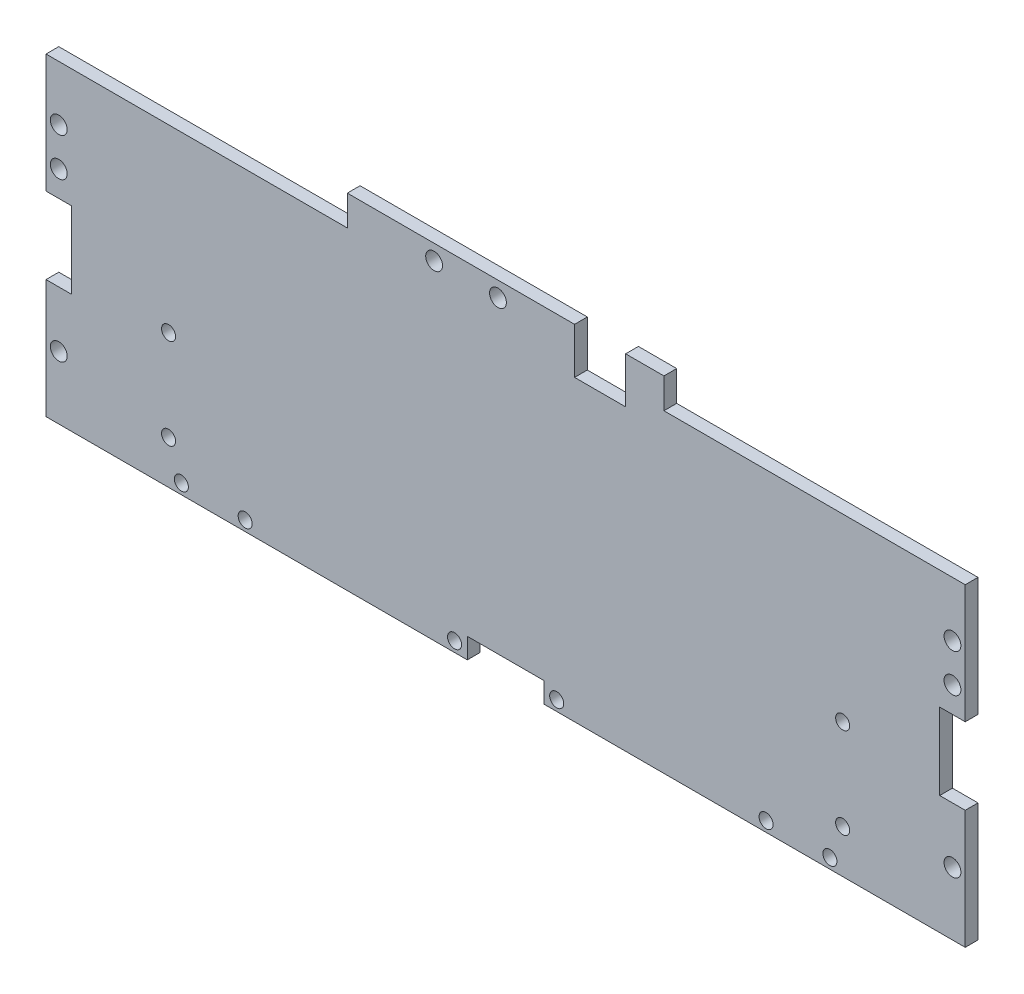
SolidWorks part; units mm, degrees
material "7075-T6, Chapa (SS)"
ref_plane "Plano frontal" through (0, 0, 0) normal (0, 0, 1) x (1, 0, 0)
ref_plane "Plano superior" through (0, 0, 0) normal (0, 1, 0) x (1, 0, 0)
ref_plane "Plano direito" through (0, 0, 0) normal (1, 0, 0) x (0, 0, -1)
sketch "Esboço1" plane through (0, 0, 0) normal (0, 0, 1) x (1, 0, 0)
  line L0 (0, 76.5) -> (0, 132.32)
  line L1 (0, 0) -> (165, 0)
  line L2 (0, 0) -> (0, 46.5)
  line L3 (116, 134.82) -> (244, 134.82)
  line L4 (360, 0) -> (360, 46.5)
  line L5 (0, 46.5) -> (10, 46.5)
  line L7 (0, 76.5) -> (10, 76.5)
  line L8 (10, 46.5) -> (10, 76.5)
  line L9 (360, 76.5) -> (360, 132.32)
  line L10 (360, 46.5) -> (350, 46.5)
  line L12 (360, 76.5) -> (350, 76.5)
  line L13 (350, 46.5) -> (350, 76.5)
  line L14 (195, 0) -> (360, 0)
  line L16 (165, 0) -> (165, 8)
  line L17 (165, 8) -> (195, 8)
  line L18 (195, 0) -> (195, 8)
  line L21 (0, 132.32) -> (0, 172.82)
  line L22 (0, 172.82) -> (116, 172.82)
  line L23 (116, 134.82) -> (116, 172.82)
  line L25 (360, 132.32) -> (360, 172.82)
  line L26 (360, 172.82) -> (244, 172.82)
  line L27 (244, 134.82) -> (244, 172.82)
  dimension "D1" = 360
  dimension "D2" = 132.32
  dimension "D3" = 10
  dimension "D4" = 30
  dimension "D5" = 46.5
  dimension "D6" = 30
  dimension "D7" = 10
  dimension "D8" = 46.5
  dimension "D9" = 8
  dimension "D10" = 30
  dimension "D11" = 128
  dimension "D12" = 40.5
  dimension "D13" = 38
extrude "Ressalto-extrusão1" add sketch "Esboço1" along normal blind 5
hole_wizard "Furo com folga de M61" positions "Esboço2" profile "Esboço3" hole size "M6" standard "ISO" end condition through all
sketch "Esboço2" plane through (-158.2782, -245.4192, 5) normal (0, 0, 1) x (-1, 0, 0)
  line L4 (-158.2782, -291.9192) -> (-158.2782, -245.4192) construction
  line L5 (-158.2782, -418.2392) -> (-158.2782, -321.9192) construction
  line L6 (-158.2782, -245.4192) -> (-323.2782, -245.4192) construction
  line L8 (-158.2782, -321.9192) -> (-168.2782, -321.9192) construction
  line L9 (-338.2782, -253.4192) -> (-338.2782, -380.2392) construction
  line L10 (-323.2782, -253.4192) -> (-353.2782, -253.4192) construction
  line L11 (-402.2782, -380.2392) -> (-274.2782, -380.2392) construction
  line L13 (-158.2782, -418.2392) -> (-158.2782, -321.9192) construction
  line L14 (-353.2782, -245.4192) -> (-518.2782, -245.4192) construction
  line L15 (-518.2782, -321.9192) -> (-518.2782, -418.2392) construction
  line L16 (-458.2782, -374.2392) -> (-218.2782, -374.2392) construction
  line L17 (-168.2782, -291.9192) -> (-158.2782, -291.9192) construction
  line L18 (-402.2782, -418.2392) -> (-402.2782, -380.2392) construction
  point P3 (-163.2782, -331.9192)
  point P54 (-163.2782, -270.0692)
  point P75 (-513.2782, -331.9192)
  point P76 (-513.2782, -270.0692)
  point P80 (-458.2782, -374.2392)
  point P82 (-428.2782, -374.2392)
  point P84 (-248.2782, -374.2392)
  point P86 (-218.2782, -374.2392)
  point P106 (-335.2782, -374.2392)
  point P121 (-163.2782, -346.9192)
  point P123 (-513.2782, -346.9192)
  point P130 (-310.2782, -374.2392)
  dimension "D2" = 21.85
  dimension "D3" = 5
  dimension "D4" = 15
  dimension "D5" = 128.82
  dimension "D6" = 5
  dimension "D7" = 10
  dimension "D8" = 5
  dimension "D9" = 67
  dimension "D10" = 25
  dimension "D11" = 128.82
  dimension "D12" = 128.82
  dimension "D13" = 128.82
  dimension "D14" = 60
  dimension "D15" = 60
  dimension "D16" = 30
  dimension "D17" = 30
sketch "Esboço3" plane through (5, 86.5, 5) normal (1, 0, 0) x (0, -1, 0)
  line L0 (0, 0) -> (0, 5)
  line L1 (0, 5) -> (3.3, 5)
  line L2 (3.3, 5) -> (3.3, 0)
  line L5 (3.3, 0) -> (0, 0)
  line L11 (0, -6.35) -> (0, 107.95) construction
  dimension "Thru Hole Dia." = 6.6
  dimension "Thru Hole Depth" = 5
hole_wizard "Furo com folga de M51" positions "Esboço4" profile "Esboço5" hole size "M5" standard "ISO" end condition through all
sketch "Esboço4" plane through (-158.2782, -245.4192, 5) normal (0, 0, 1) x (-1, 0, 0)
  line L0 (-470.2782, -262.4192) -> (-470.2782, -297.9192) construction
  line L1 (-470.2782, -297.9564) -> (-470.2782, -297.9192) construction
  line L2 (-206.2782, -262.4192) -> (-206.2782, -297.9192) construction
  line L5 (-518.2782, -245.4192) -> (-518.2782, -291.9192) construction
  line L6 (-158.2782, -291.9192) -> (-158.2782, -245.4192) construction
  line L8 (-353.2782, -245.4192) -> (-518.2782, -245.4192) construction
  line L9 (-158.2782, -245.4192) -> (-323.2782, -245.4192) construction
  line L11 (-518.2782, -249.4192) -> (-158.2782, -249.4192) construction
  line L12 (-518.2782, -245.4192) -> (-518.2782, -291.9192) construction
  line L14 (-353.2782, -253.4192) -> (-353.2782, -245.4192) construction
  line L15 (-323.2782, -245.4192) -> (-323.2782, -253.4192) construction
  point P0 (-470.2782, -297.9192)
  point P6 (-470.2782, -262.4192)
  point P12 (-206.2782, -297.9192)
  point P15 (-206.2782, -262.4192)
  point P78 (-465.2782, -249.4192)
  point P80 (-440.2782, -249.4192)
  point P82 (-358.2782, -249.4192)
  point P84 (-318.2782, -249.4192)
  point P86 (-236.2782, -249.4192)
  point P88 (-211.2782, -249.4192)
  dimension "D1" = 48
  dimension "D2" = 48
  dimension "D3" = 17
  dimension "D4" = 17
  dimension "D5" = 35.5
  dimension "D7" = 35.5
  dimension "D11" = 4
  dimension "D12" = 53
  dimension "D13" = 5
  dimension "D14" = 5
  dimension "D15" = 53
  dimension "D16" = 25
  dimension "D17" = 25
sketch "Esboço5" plane through (312, 52.5, 5) normal (1, 0, 0) x (0, -1, 0)
  line L0 (0, 0) -> (0, 5)
  line L1 (0, 5) -> (2.75, 5)
  line L2 (2.75, 5) -> (2.75, 0)
  line L3 (2.75, 0) -> (0, 0)
  line L4 (0, -6.35) -> (0, 107.95) construction
  dimension "Thru Hole Dia." = 5.5
  dimension "Thru Hole Depth" = 5
sketch "Esboço15" plane through (0, 0, 5) normal (0, 0, 1) x (1, 0, 0)
  line L0 (100, 172.82) -> (100, 212.82)
  line L1 (116, 172.82) -> (0, 172.82) construction
  line L2 (100, 212.82) -> (0, 172.82)
  line L3 (260, 172.82) -> (260, 212.82)
  line L4 (360, 172.82) -> (244, 172.82) construction
  line L5 (260, 212.82) -> (360, 172.82)
  line L6 (360, 172.82) -> (260, 172.82)
  line L7 (100, 172.82) -> (0, 172.82)
  dimension "D1" = 40
  dimension "D2" = 100
  dimension "D3" = 100
extrude "Ressalto-extrusão3" add sketch "Esboço15" against normal through all
sketch "Esboço18" plane through (0, 0, 5) normal (0, 0, 1) x (1, 0, 0)
  line L0 (118, 134.82) -> (118, 123)
  line L1 (118, 123) -> (0, 123)
  line L2 (0, 172.82) -> (0, 76.5) construction
  line L3 (0, 123) -> (0, 223)
  line L4 (0, 223) -> (360, 223)
  line L5 (360, 223) -> (360, 123)
  line L6 (360, 76.5) -> (360, 172.82) construction
  line L7 (360, 123) -> (242, 123)
  line L8 (242, 123) -> (242, 134.82)
  line L9 (242, 134.82) -> (118, 134.82)
  line L11 (0, 0) -> (165, 0) construction
  line L12 (195, 0) -> (360, 0) construction
  dimension "D1" = 123
  dimension "D2" = 123
  dimension "D3" = 100
  dimension "D4" = 124
  dimension "D5" = 118
  dimension "D6" = 88.18
extrude "Corte-extrusão1" cut sketch "Esboço18" against normal through all
sketch "Esboço19" plane through (0, 0, 5) normal (0, 0, 1) x (1, 0, 0)
  line L0 (227, 134.82) -> (227, 116.82)
  line L1 (242, 134.82) -> (118, 134.82) construction
  line L2 (227, 116.82) -> (207, 116.82)
  line L3 (207, 116.82) -> (207, 134.82)
  line L4 (207, 134.82) -> (227, 134.82)
  line L5 (242, 134.82) -> (242, 123) construction
  dimension "D1" = 15
  dimension "D2" = 20
  dimension "D3" = 18
extrude "Corte-extrusão2" cut sketch "Esboço19" against normal through all
